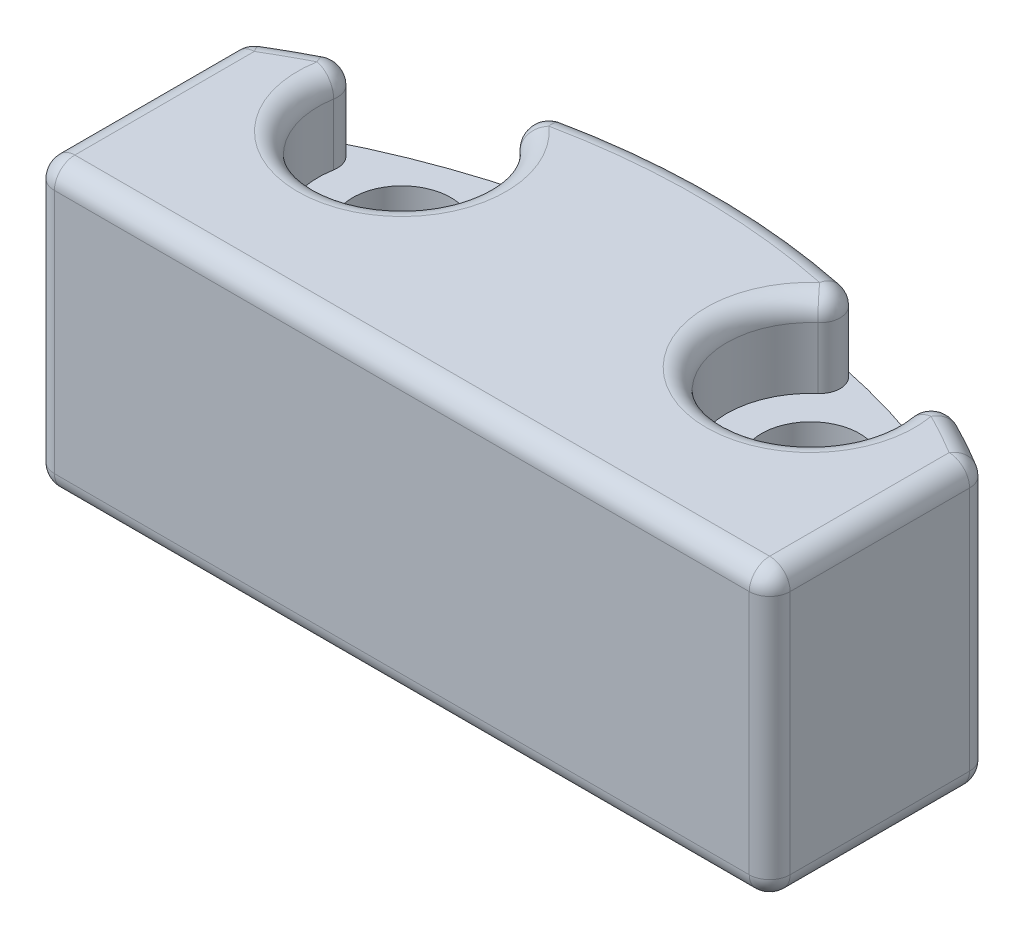
SolidWorks part; units mm, degrees
ref_plane "Front Plane" through (0, 0, 0) normal (0, 0, 1) x (1, 0, 0)
ref_plane "Top Plane" through (0, 0, 0) normal (0, 1, 0) x (1, 0, 0)
ref_plane "Right Plane" through (0, 0, 0) normal (1, 0, 0) x (0, 0, -1)
sketch "Sketch1" plane through (0, 0, 0) normal (0, 1, 0) x (1, 0, 0)
  line L0 (9, -5.17) -> (9, 2.5778) construction
  line L2 (0, 0) -> (0, -5.17)
  line L3 (0, -5.17) -> (18, -5.17)
  line L4 (18, 0) -> (18, -5.17)
  arc A0 (0, 0) -> (18, 0) centre (9, -14.4222) cw
  circle A1 centre (4, -0.17) radius 1.2
  circle A2 centre (14, -0.17) radius 1.2
  dimension "D2" = 17
  dimension "D4" = 10
  dimension "D5" = 2.4
  dimension "D6" = 2.4
  dimension "D1" = 18
  dimension "D3" = 5.17
  dimension "D7" = 5
extrude "Boss-Extrude1" add sketch "Sketch1" along normal blind 7
sketch "Sketch2" plane through (0, 7, 0) normal (0, 1, 0) x (1, 0, 0)
  circle A0 centre (4, -0.17) radius 2.05
  circle A1 centre (14, -0.17) radius 2.05
  dimension "D1" = 4.1
  dimension "D2" = 4.1
extrude "Cut-Extrude1" cut sketch "Sketch2" against normal blind 2
fillet "Fillet1" radius 0.5 20 edges at (0, 3.5, 0) (0, 0, 2.585) (18, 3.5, 0) (18, 0, 2.585) (0, 3.5, 5.17) (18, 3.5, 5.17) (9, 0, 5.17) (13.3214, 7, 2.1044) (16.7289, 7, -0.7193) (18, 7, 2.585) (9, 7, 5.17) (0, 7, 2.585) (1.2711, 7, -0.7193) (4.6786, 7, 2.1044) (9, 7, -2.5778) (4.1587, 6, -1.8739) (2.5992, 6, -1.3268) (13.8413, 6, -1.8739) (15.4008, 6, -1.3268) (9, 0, -2.5778)
